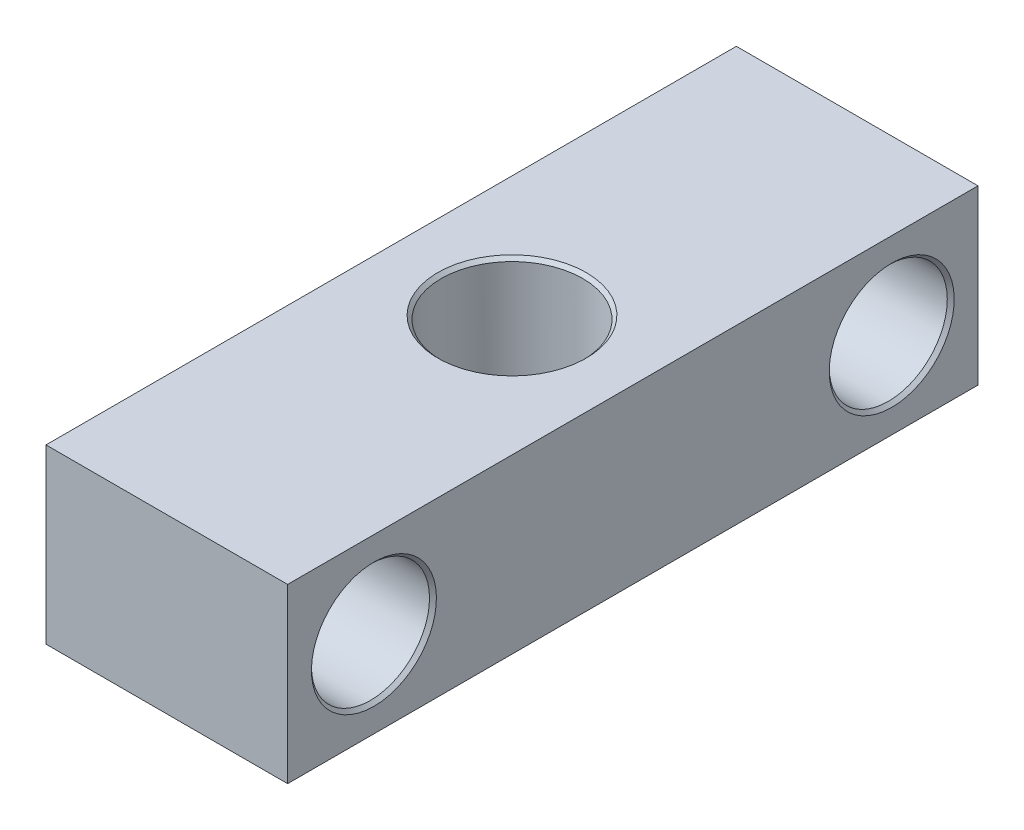
SolidWorks part; units mm, degrees
material "Gomma"
ref_plane "Piano frontale" through (0, 0, 0) normal (0, 0, 1) x (1, 0, 0)
ref_plane "Piano superiore" through (0, 0, 0) normal (0, 1, 0) x (1, 0, 0)
ref_plane "Piano destro" through (0, 0, 0) normal (1, 0, 0) x (0, 0, -1)
sketch "Schizzo1" plane through (0, 0, 0) normal (0, 0, 1) x (1, 0, 0)
  line L1 (-17.5, 12.5) -> (17.5, 12.5)
  line L2 (-17.5, 12.5) -> (-17.5, -12.5)
  line L3 (-17.5, -12.5) -> (17.5, -12.5)
  line L4 (17.5, 12.5) -> (17.5, -12.5)
  line L5 (-17.5, 12.5) -> (17.5, -12.5) construction
  line L6 (-17.5, -12.5) -> (17.5, 12.5) construction
  point P0 (0, 0)
  dimension "D1" = 35
  dimension "D2" = 25
extrude "Estrusione-Estrusione1" add sketch "Schizzo1" along normal mid plane 100
sketch "Schizzo2" plane through (0, 12.5, 0) normal (0, 1, 0) x (1, 0, 0)
  circle A0 centre (0, 0) radius 10.25
  dimension "D1" = 20.5
extrude "Taglio-Estrusione1" cut sketch "Schizzo2" against normal blind 100
sketch "Schizzo3" plane through (17.5, 0, 0) normal (1, 0, 0) x (0, 0, -1)
  line L0 (50, -12.5) -> (50, 12.5) construction
  line L1 (-50, 12.5) -> (50, 12.5) construction
  line L3 (-50, -12.5) -> (-50, 12.5) construction
  circle A0 centre (37.5, 0) radius 8.55
  circle A1 centre (-37.5, 0) radius 8.55
  dimension "D3" = 17.1
  dimension "D4" = 17.1
  dimension "D1" = 12.5
  dimension "D2" = 12.5
  dimension "D5" = 12.5
  dimension "D6" = 12.5
extrude "Taglio-Estrusione3" cut sketch "Schizzo3" against normal through all
chamfer "Smusso1" distance 0.5 angle 45 6 edges at (-17.5, 8.55, -37.5) (-17.5, 8.55, 37.5) (0, 12.5, 10.25) (0, -12.5, 10.25) (17.5, 8.55, -37.5) (17.5, 8.55, 37.5)
